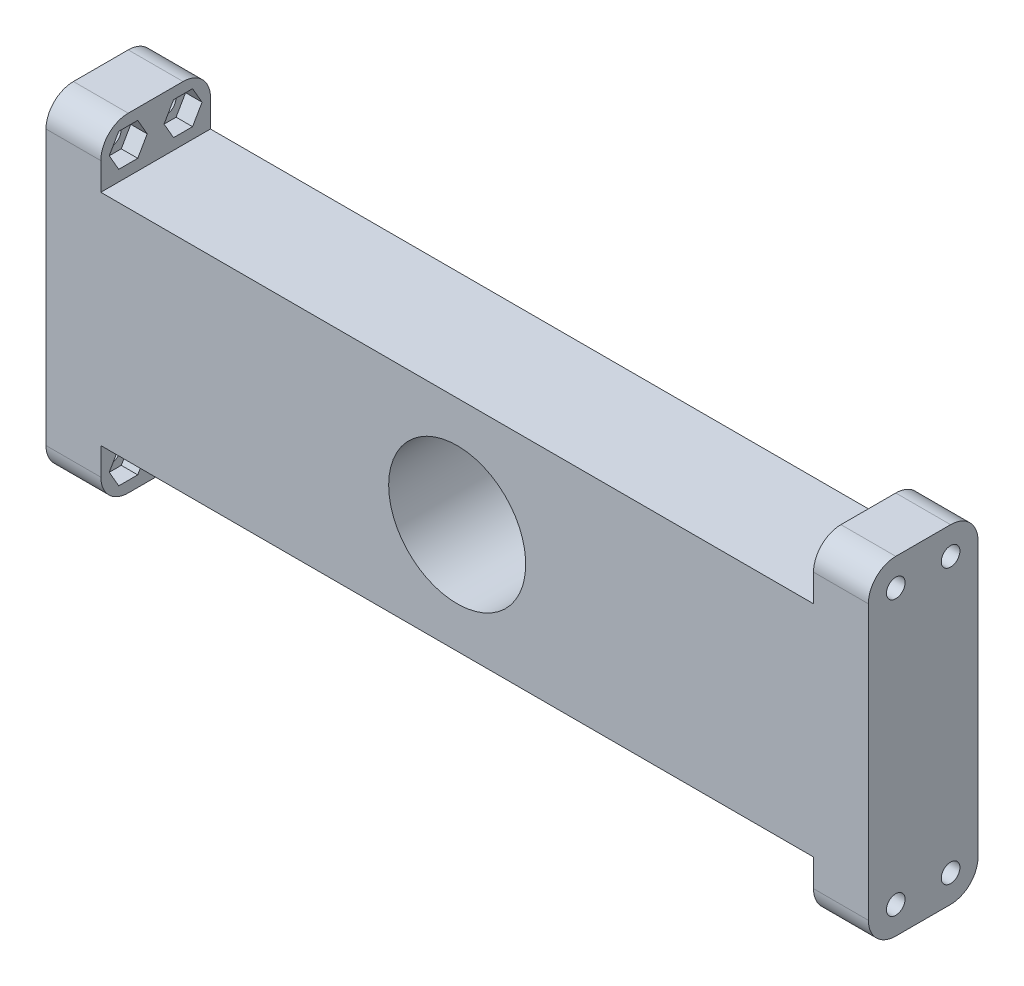
SolidWorks part; units mm, degrees
material "ESUN PLA +"
ref_plane "Front Plane" through (0, 0, 0) normal (0, 0, 1) x (1, 0, 0)
ref_plane "Top Plane" through (0, 0, 0) normal (0, 1, 0) x (1, 0, 0)
ref_plane "Right Plane" through (0, 0, 0) normal (1, 0, 0) x (0, 0, -1)
sketch "Sketch1" plane through (0, 0, 0) normal (0, 0, 1) x (1, 0, 0)
  line L1 (-75, -30) -> (75, -30)
  line L2 (-75, -30) -> (-75, 30)
  line L3 (-75, 30) -> (75, 30)
  line L4 (75, -30) -> (75, 30)
  line L5 (-75, -30) -> (75, 30) construction
  line L6 (-75, 30) -> (75, -30) construction
  point P0 (0, 0)
  dimension "D1" = 150
  dimension "D2" = 60
extrude "Boss-Extrude1" add sketch "Sketch1" along normal mid plane 20
sketch "Sketch2" plane through (0, 0, 10) normal (0, 0, 1) x (1, 0, 0)
  line L0 (-75, -30) -> (75, -30) construction
  line L1 (-65, -30) -> (65, -30)
  line L2 (-65, -30) -> (-65, -20)
  line L3 (-65, -20) -> (65, -20)
  line L4 (65, -30) -> (65, -20)
  line L5 (75, 30) -> (-75, 30) construction
  line L6 (65, 30) -> (-65, 30)
  line L7 (65, 30) -> (65, 20)
  line L8 (65, 20) -> (-65, 20)
  line L9 (-65, 30) -> (-65, 20)
  line L11 (-75, 30) -> (-75, -30) construction
  line L12 (75, -30) -> (75, 30) construction
  dimension "D1" = 10
  dimension "D2" = 10
  dimension "D3" = 10
extrude "Cut-Extrude1" cut sketch "Sketch2" against normal through all both and the other way through all
fillet "Fillet1" radius 5 8 edges at (70, 30, -10) (70, 30, 10) (70, -30, 10) (70, -30, -10) (-70, -30, -10) (-70, -30, 10) (-70, 30, -10) (-70, 30, 10)
sketch "Sketch4" plane through (65, 0, 0) normal (-1, 0, 0) x (0, 0, 1)
  line L0 (-10, 20) -> (-10, 25) construction
  line L1 (-5, 30) -> (5, 30) construction
  circle A0 centre (-5, 25) radius 1.7
  dimension "D1" = 5
  dimension "D3" = 3.4
  dimension "D2" = 5
extrude "Cut-Extrude3" cut sketch "Sketch4" against normal through all both and the other way through all
sketch "Sketch5" plane through (65, 0, 0) normal (-1, 0, 0) x (0, 0, 1)
  line L1 (-8.4641, 25) -> (-6.7321, 22)
  line L2 (-6.7321, 22) -> (-3.2679, 22)
  line L3 (-3.2679, 22) -> (-1.5359, 25)
  line L4 (-1.5359, 25) -> (-3.2679, 28)
  line L5 (-3.2679, 28) -> (-6.7321, 28)
  line L6 (-6.7321, 28) -> (-8.4641, 25)
  circle A0 centre (-5, 25) radius 3 construction
  circle A1 centre (-5, 25) radius 1.7 construction
  dimension "D1" = 6
extrude "Cut-Extrude4" cut sketch "Sketch5" against normal blind 3
mirror "Mirror1" about plane through (0, 0, 0) normal (1, 0, 0) of "Cut-Extrude4", "Cut-Extrude3" second plane through (0, 0, 0) second plane normal (0, 0, 1)
mirror "Mirror2" about plane through (0, 0, 0) normal (0, 1, 0) of "Mirror1", "Cut-Extrude4"
sketch "Sketch6" plane through (0, 0, -10) normal (0, 0, -1) x (-1, 0, 0)
  circle A0 centre (0, 0) radius 12.5
  dimension "D1" = 25
extrude "Cut-Extrude5" cut sketch "Sketch6" against normal through all
